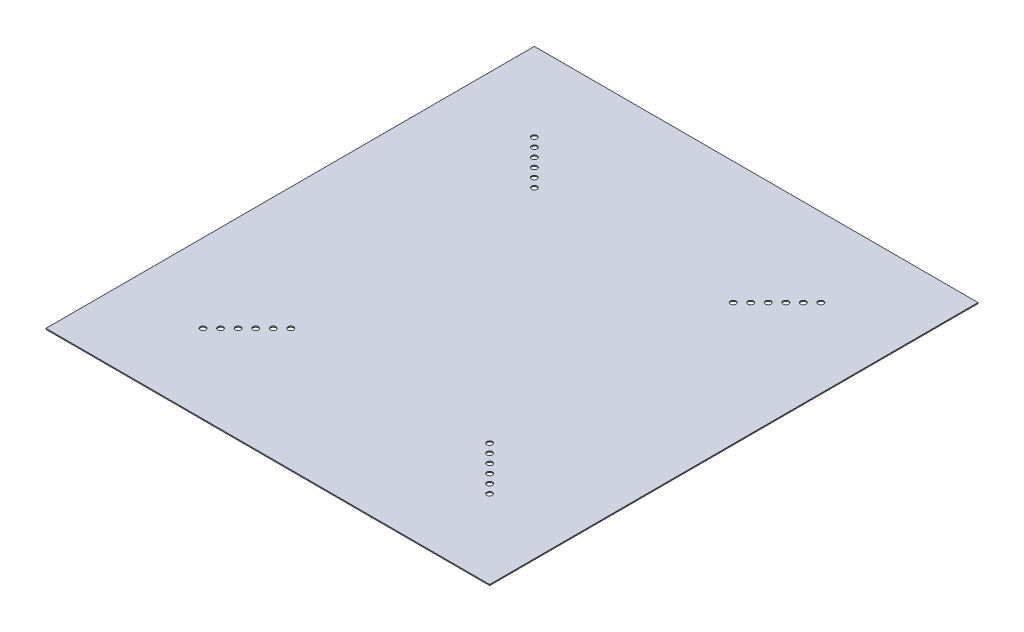
SolidWorks part; units mm, degrees
ref_plane "Front Plane" through (0, 0, 0) normal (0, 0, 1) x (1, 0, 0)
ref_plane "Top Plane" through (0, 0, 0) normal (0, 1, 0) x (1, 0, 0)
ref_plane "Right Plane" through (0, 0, 0) normal (1, 0, 0) x (0, 0, -1)
sketch "Sketch3" plane through (0, 0, 0) normal (0, 1, 0) x (1, 0, 0)
  line L4 (-57.0395, 93.017) -> (57.0395, 93.017)
  line L5 (57.0395, 93.017) -> (110.0725, 146.05)
  line L14 (110.0725, 146.05) -> (128.033, 128.0895)
  line L15 (128.033, 128.0895) -> (75, 75.0565)
  line L16 (75, 75.0565) -> (75, 0)
  line L17 (0, 0) -> (0, 93.017) construction
  line L18 (0, 0) -> (75, 0) construction
  line L19 (-75, 75.0565) -> (-75, -75.0565)
  line L20 (-128.033, 128.0895) -> (-75, 75.0565)
  line L21 (-110.0725, 146.05) -> (-128.033, 128.0895)
  line L22 (-57.0395, 93.017) -> (-110.0725, 146.05)
  line L23 (-57.0395, -93.017) -> (-110.0725, -146.05)
  line L24 (-110.0725, -146.05) -> (-128.033, -128.0895)
  line L25 (-128.033, -128.0895) -> (-75, -75.0565)
  line L26 (75, -75.0565) -> (75, 0)
  line L27 (128.033, -128.0895) -> (75, -75.0565)
  line L28 (110.0725, -146.05) -> (128.033, -128.0895)
  line L29 (57.0395, -93.017) -> (110.0725, -146.05)
  line L30 (-57.0395, -93.017) -> (57.0395, -93.017)
  point P5 (75, 37.5282)
  point P18 (-75, 0)
  dimension "D1" = 25.4
  dimension "D2" = 75
  dimension "D4" = 75
  dimension "D5" = 135
  dimension "D3" = 292.1
extrude "Sheet" add sketch "Sketch3" along normal blind 0.7937
fillet "Fillet1" radius 50 8 edges at (-75, 0.3969, 75.0565) (-57.0395, 0.3969, 93.017) (75, 0.3969, 75.0565) (57.0395, 0.3969, 93.017) (57.0395, 0.3969, -93.017) (75, 0.3969, -75.0565) (-75, 0.3969, -75.0565) (-57.0395, 0.3969, -93.017)
hole_wizard "M4 Clearance Hole1" positions "Sketch4" profile "Sketch5" hole size "M4" standard "ANSI Metric" end condition through all
sketch "Sketch4" plane through (0, 0.7937, 0) normal (0, 1, 0) x (1, 0, 0)
  line L0 (119.0528, 137.0697) -> (55.6644, 73.6814) construction
  line L1 (128.033, 128.0895) -> (110.0725, 146.05) construction
  line L2 (36.3288, 93.017) -> (75, 54.3458) construction
  point P0 (115.5172, 133.5342)
  point P15 (55.6644, 73.6814)
  dimension "D1" = 5
sketch "Sketch5" plane through (115.5172, 0.7937, -133.5342) normal (1, 0, 0) x (0, 0, 1)
  line L0 (0, 0) -> (0, 0.7937)
  line L1 (0, 0.7937) -> (2.25, 0.7937)
  line L2 (2.25, 0.7937) -> (2.25, 0)
  line L5 (2.25, 0) -> (0, 0)
  line L11 (0, -6.35) -> (0, 107.95) construction
  dimension "Thru Hole Dia." = 4.5
  dimension "Thru Hole Depth" = 0.7937
pattern_linear "LPattern1" count 6 spacing 10 along (-0.7071, 0, 0.7071) of "M4 Clearance Hole1"
mirror "Mirror1" about plane through (0, 0, 0) normal (0, 0, 1) of "LPattern1", "M4 Clearance Hole1"
mirror "Mirror2" about plane through (0, 0, 0) normal (1, 0, 0) of "Mirror1", "M4 Clearance Hole1", "LPattern1"
sketch "Sketch6" plane through (0, 0.7937, 0) normal (0, 1, 0) x (1, 0, 0)
  line L0 (-128.033, 128.0895) -> (-128.033, -128.0895)
  line L2 (-89.6447, -89.7011) -> (-128.033, -128.0895) construction
  line L3 (-110.0725, -146.05) -> (110.0725, -146.05)
  line L4 (128.033, 128.0895) -> (128.033, -128.0895)
  line L5 (89.6447, 89.7011) -> (128.033, 128.0895) construction
  line L6 (75, -54.3458) -> (75, 54.3458) construction
  line L7 (128.033, -128.0895) -> (89.6447, -89.7011) construction
  line L8 (71.6841, -107.6617) -> (110.0725, -146.05) construction
  line L9 (-36.3288, -93.017) -> (36.3288, -93.017) construction
  line L10 (-110.0725, -146.05) -> (-71.6841, -107.6617) construction
  line L11 (-75, 54.3458) -> (-75, -54.3458) construction
  line L12 (-128.033, 128.0895) -> (-89.6447, 89.7011) construction
  line L13 (89.6447, 89.7011) -> (128.033, 128.0895)
  line L14 (75, -54.3458) -> (75, 54.3458)
  line L15 (128.033, -128.0895) -> (89.6447, -89.7011)
  line L16 (71.6841, -107.6617) -> (110.0725, -146.05)
  line L17 (-36.3288, -93.017) -> (36.3288, -93.017)
  line L18 (-110.0725, -146.05) -> (-71.6841, -107.6617)
  line L19 (-89.6447, -89.7011) -> (-128.033, -128.0895)
  line L20 (-75, 54.3458) -> (-75, -54.3458)
  line L21 (-128.033, 128.0895) -> (-89.6447, 89.7011)
  arc A0 (89.6447, 89.7011) -> (75, 54.3458) centre (125, 54.3458) ccw construction
  arc A1 (75, -54.3458) -> (89.6447, -89.7011) centre (125, -54.3458) ccw construction
  arc A2 (71.6841, -107.6617) -> (36.3288, -93.017) centre (36.3288, -143.017) ccw construction
  arc A3 (-36.3288, -93.017) -> (-71.6841, -107.6617) centre (-36.3288, -143.017) ccw construction
  arc A4 (-89.6447, -89.7011) -> (-75, -54.3458) centre (-125, -54.3458) ccw construction
  arc A5 (-75, 54.3458) -> (-89.6447, 89.7011) centre (-125, 54.3458) ccw construction
  arc A6 (89.6447, 89.7011) -> (75, 54.3458) centre (125, 54.3458) ccw
  arc A7 (75, -54.3458) -> (89.6447, -89.7011) centre (125, -54.3458) ccw
  arc A8 (71.6841, -107.6617) -> (36.3288, -93.017) centre (36.3288, -143.017) ccw
  arc A9 (-36.3288, -93.017) -> (-71.6841, -107.6617) centre (-36.3288, -143.017) ccw
  arc A10 (-89.6447, -89.7011) -> (-75, -54.3458) centre (-125, -54.3458) ccw
  arc A11 (-75, 54.3458) -> (-89.6447, 89.7011) centre (-125, 54.3458) ccw
extrude "FullSheetSideFlaps" add sketch "Sketch6" against normal up to surface (0.7937 mm away) up to face at (-87.2329, 0, -102.9999)
sketch "Sketch8" [suppressed] plane through (0, 0.7937, 0) normal (0, 1, 0) x (1, 0, 0)
  line L0 (-128.033, 128.0895) -> (-128.033, -128.0895)
  line L1 (-128.033, -128.0895) -> (-106.5774, -49.6627)
  line L2 (-103.033, -23.2749) -> (-103.033, 23.2749)
  line L3 (-106.5774, 49.6627) -> (-128.033, 128.0895)
  line L4 (0, -0.4366) -> (0, 0.4366) construction
  line L5 (106.5774, 49.6627) -> (128.033, 128.0895)
  line L6 (103.033, -23.2749) -> (103.033, 23.2749)
  line L7 (128.033, -128.0895) -> (106.5774, -49.6627)
  line L8 (128.033, 128.0895) -> (128.033, -128.0895)
  line L9 (-110.0725, -146.05) -> (110.0725, -146.05)
  line L10 (110.0725, -146.05) -> (39.1925, -121.05)
  line L11 (39.1925, -121.05) -> (-39.1925, -121.05)
  line L12 (-39.1925, -121.05) -> (-110.0725, -146.05)
  arc A0 (-103.033, 23.2749) -> (-106.5774, 49.6627) centre (-203.033, 23.2749) ccw
  arc A1 (-106.5774, -49.6627) -> (-103.033, -23.2749) centre (-203.033, -23.2749) ccw
  arc A2 (106.5774, -49.6627) -> (103.033, -23.2749) centre (203.033, -23.2749) cw
  arc A3 (103.033, 23.2749) -> (106.5774, 49.6627) centre (203.033, 23.2749) cw
  point P11 (-103.033, 0)
  point P27 (0, -121.05)
  dimension "D1" = 100
  dimension "D2" = 100
  dimension "D3" = 25
  dimension "D4" = 25
extrude "ReducedFlap" [suppressed] cut sketch "Sketch8" against normal up to next
sketch "Sketch9" plane through (0, 0.7937, 0) normal (0, 1, 0) x (1, 0, 0)
  line L0 (110.0725, 146.05) -> (71.6841, 107.6617) construction
  line L1 (36.3288, 93.017) -> (-36.3288, 93.017) construction
  line L2 (-71.6841, 107.6617) -> (-110.0725, 146.05) construction
  line L3 (110.0725, 146.05) -> (71.6841, 107.6617)
  line L4 (36.3288, 93.017) -> (-36.3288, 93.017)
  line L5 (-71.6841, 107.6617) -> (-110.0725, 146.05)
  line L6 (-110.0725, 146.05) -> (110.0725, 146.05)
  arc A0 (36.3288, 93.017) -> (71.6841, 107.6617) centre (36.3288, 143.017) ccw construction
  arc A1 (-71.6841, 107.6617) -> (-36.3288, 93.017) centre (-36.3288, 143.017) ccw construction
  arc A2 (36.3288, 93.017) -> (71.6841, 107.6617) centre (36.3288, 143.017) ccw
  arc A3 (-71.6841, 107.6617) -> (-36.3288, 93.017) centre (-36.3288, 143.017) ccw
extrude "CloseCannulusSide" add sketch "Sketch9" against normal up to surface (0.7937 mm away) up to face at (0, 0, -32.8604)
sketch "Sketch10" plane through (0, 0.7937, 0) normal (0, 1, 0) x (1, 0, 0)
  line L0 (128.033, 128.0895) -> (110.0725, 146.05) construction
  line L1 (110.0725, -146.05) -> (128.033, -128.0895) construction
  line L2 (128.033, -128.0895) -> (128.033, 128.0895) construction
  line L3 (-110.0725, -146.05) -> (110.0725, -146.05) construction
  line L4 (-128.033, -128.0895) -> (-110.0725, -146.05) construction
  line L5 (-128.033, 128.0895) -> (-128.033, -128.0895) construction
  line L6 (-110.0725, 146.05) -> (-128.033, 128.0895) construction
  line L7 (110.0725, 146.05) -> (-110.0725, 146.05) construction
  line L8 (128.033, 128.0895) -> (110.0725, 146.05)
  line L9 (110.0725, -146.05) -> (128.033, -128.0895)
  line L10 (128.033, -128.0895) -> (128.033, 128.0895)
  line L11 (-110.0725, -146.05) -> (110.0725, -146.05)
  line L12 (-128.033, -128.0895) -> (-110.0725, -146.05)
  line L13 (-128.033, 128.0895) -> (-128.033, -128.0895)
  line L14 (-110.0725, 146.05) -> (-128.033, 128.0895)
  line L15 (110.0725, 146.05) -> (-110.0725, 146.05)
  line L17 (-178.833, -196.85) -> (178.833, -196.85)
  line L18 (-178.833, -196.85) -> (-178.833, 196.85)
  line L19 (-178.833, 196.85) -> (178.833, 196.85)
  line L20 (178.833, -196.85) -> (178.833, 196.85)
  line L21 (-178.833, -196.85) -> (178.833, 196.85) construction
  line L22 (-178.833, 196.85) -> (178.833, -196.85) construction
  point P4 (0, 0)
  dimension "D1" = 50.8
  dimension "D2" = 50.8
extrude "ExcessAllSides" add sketch "Sketch10" against normal up to surface (0.7937 mm away) up to face at (0, 0, 0)
equation "\"SheetLength\"= 258"
equation "\"D2@Sketch3\"=\"SheetWidth\" / 2 - \"SheetEdgeOffset\""
equation "\"SheetWidth\"=200"
equation "\"TabLength\"=75"
equation "\"D4@Sketch3\"= \"TabLength\""
equation "\"SheetEdgeOffset\"= 25mm"
equation "\"RawSheetSize\"=304.8"
equation "\"D3@Sketch3\"=\"RawSheetSize\" - \"SlopForLaserCutting\""
equation "\"SlopForLaserCutting\"= 0.5in"
equation "\"FlapDepth\"=25"
equation "\"D3@Sketch8\"=\"FlapDepth\""
equation "\"D4@Sketch8\"=\"FlapDepth\""
equation "\"D1@Sketch10\"=2in"
equation "\"D2@Sketch10\"=2in"
